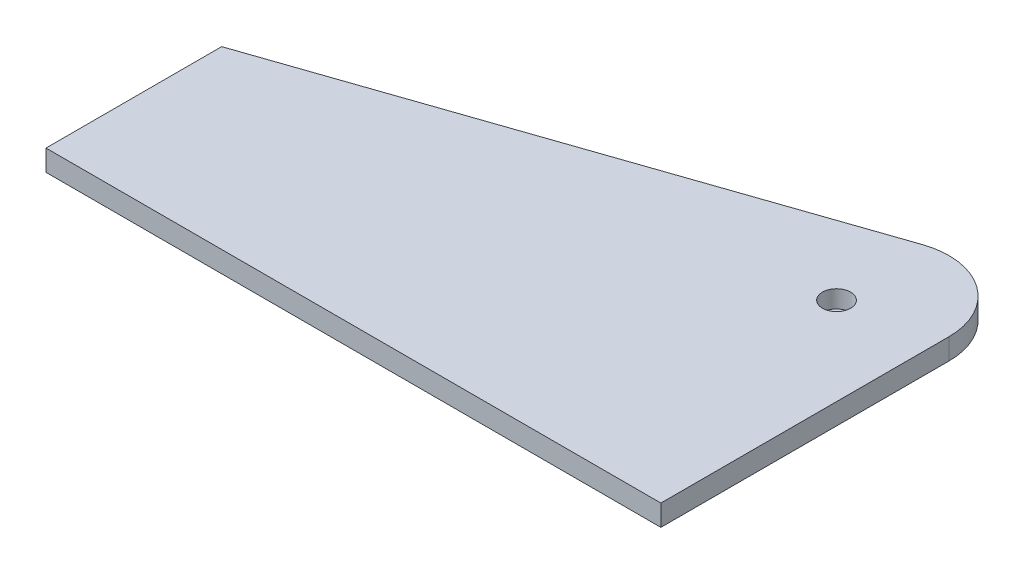
SolidWorks part; units mm, degrees
ref_plane "Front Plane" through (0, 0, 0) normal (0, 0, 1) x (1, 0, 0)
ref_plane "Top Plane" through (0, 0, 0) normal (0, 1, 0) x (1, 0, 0)
ref_plane "Right Plane" through (0, 0, 0) normal (1, 0, 0) x (0, 0, -1)
sketch "Sketch4" plane through (0, 0, 0) normal (0, 1, 0) x (1, 0, 0)
  line L3 (-87.5, -50) -> (87.5, -50)
  line L4 (87.5, 0) -> (87.5, -50)
  line L7 (-87.5, -50) -> (-87.5, 0)
  line L10 (-87.5, 0) -> (87.5, 60.0061)
  line L11 (87.5, 0) -> (87.5, 60.0061)
  point P0 (0, 0)
  dimension "D1" = 175
extrude "Boss-Extrude1" add sketch "Sketch4" along normal blind 6
sketch "Sketch5" plane through (0, 6, 0) normal (0, 1, 0) x (1, 0, 0)
  line L0 (87.5, -50) -> (87.5, 60.0061) construction
  circle A0 centre (62.5, 25) radius 12.25
  dimension "D3" = 24.5
  dimension "D1" = 25
sketch "Sketch6" plane through (0, 0, 0) normal (0, -1, 0) x (-1, 0, 0)
  line L0 (-87.5, -50) -> (-87.5, 60.0061) construction
  circle A0 centre (-62.5, 25) radius 20
  dimension "D1" = 25
sketch "Sketch7" plane through (0, 6, 0) normal (0, 1, 0) x (1, 0, 0)
  circle A0 centre (62.5, 25) radius 4
fillet "Fillet2" radius 20 1 edges at (87.5, 3, -60.0061)
extrude "Cut-Extrude3" cut sketch "Sketch7" against normal blind 5 contours A0
